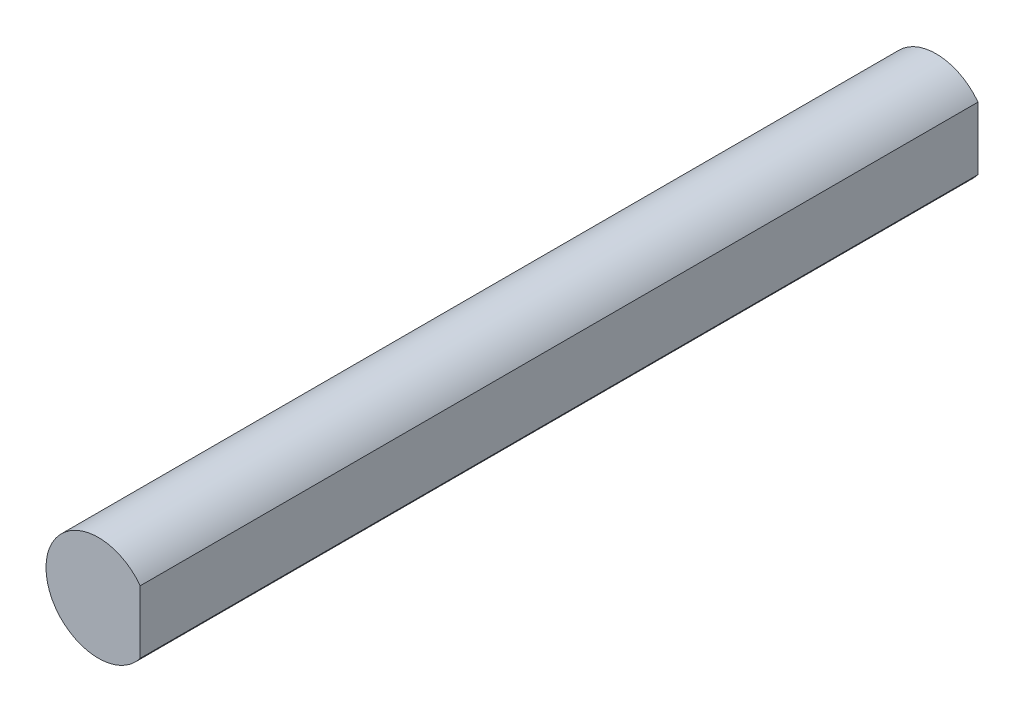
SolidWorks part; units mm, degrees
ref_plane "Plan de face" through (0, 0, 0) normal (0, 0, 1) x (1, 0, 0)
ref_plane "Plan de dessus" through (0, 0, 0) normal (0, 1, 0) x (1, 0, 0)
ref_plane "Plan de droite" through (0, 0, 0) normal (1, 0, 0) x (0, 0, -1)
sketch "Esquisse1" plane through (0, 0, 0) normal (0, 0, 1) x (1, 0, 0)
  circle A0 centre (0, 0) radius 3.175
  dimension "D1" = 6.35
extrude "Boss.-Extru.1" add sketch "Esquisse1" along normal blind 50.8
sketch "Esquisse2" plane through (0, 0, 0) normal (0, 0, -1) x (-1, 0, 0)
  line L0 (-4.6205, 3.1497) -> (-2.54, 3.1497)
  line L1 (-2.54, 3.1497) -> (-2.54, -3.2845)
  line L2 (-2.54, -3.2845) -> (-4.6205, -3.2845)
  line L3 (-4.6205, -3.2845) -> (-4.6205, 3.1497)
  dimension "D1" = 2.54
extrude "Enlèv. mat.-Extru.1" cut sketch "Esquisse2" against normal up to next
